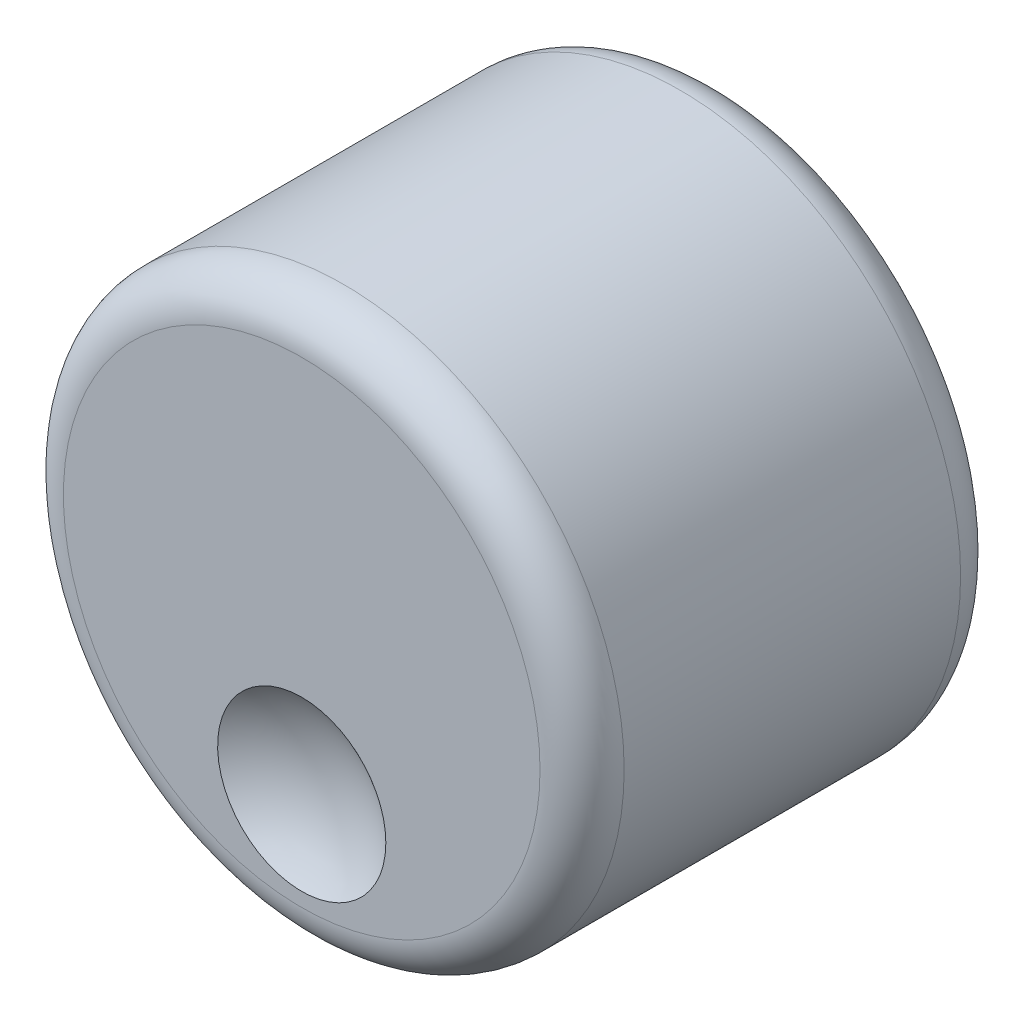
SolidWorks part; units mm, degrees
material "ABS"
ref_plane "Front Plane" through (0, 0, 0) normal (0, 0, 1) x (1, 0, 0)
ref_plane "Top Plane" through (0, 0, 0) normal (0, 1, 0) x (1, 0, 0)
ref_plane "Right Plane" through (0, 0, 0) normal (1, 0, 0) x (0, 0, -1)
sketch "Sketch1" plane through (0, 0, 0) normal (0, 0, 1) x (1, 0, 0)
  circle A0 centre (0, 0) radius 10
  dimension "D1" = 20
extrude "Boss-Extrude1" add sketch "Sketch1" along normal blind 15
fillet "Fillet1" radius 1.5 2 edges at (10, 0, 0) (10, 0, 15)
sketch "Sketch2" plane through (0, 0, 0) normal (0, 0, -1) x (-1, 0, 0)
  circle A0 centre (0, 0) radius 3
  dimension "D1" = 6
extrude "Cut-Extrude1" cut sketch "Sketch2" against normal blind 12
chamfer "Chamfer1" distance 1 angle 45 1 edges at (-3, 0, 0)
sketch "Sketch3" plane through (0, 0, 0) normal (1, 0, 0) x (0, 0, -1)
  line L0 (-13.5, -10) -> (-1.5, -10) construction
  line L1 (-15, 8.5) -> (-15, -8.5) construction
  line L2 (-24, -5) -> (-14, -5) construction
  line L3 (-24, -5) -> (-14, -5)
  arc A0 (-24, -5) -> (-14, -5) centre (-19, -5) ccw
  dimension "D1" = 10
  dimension "D2" = 5
  dimension "D3" = 4
revolve "Cut-Revolve2" cut sketch "Sketch3" angle 360 about L2
